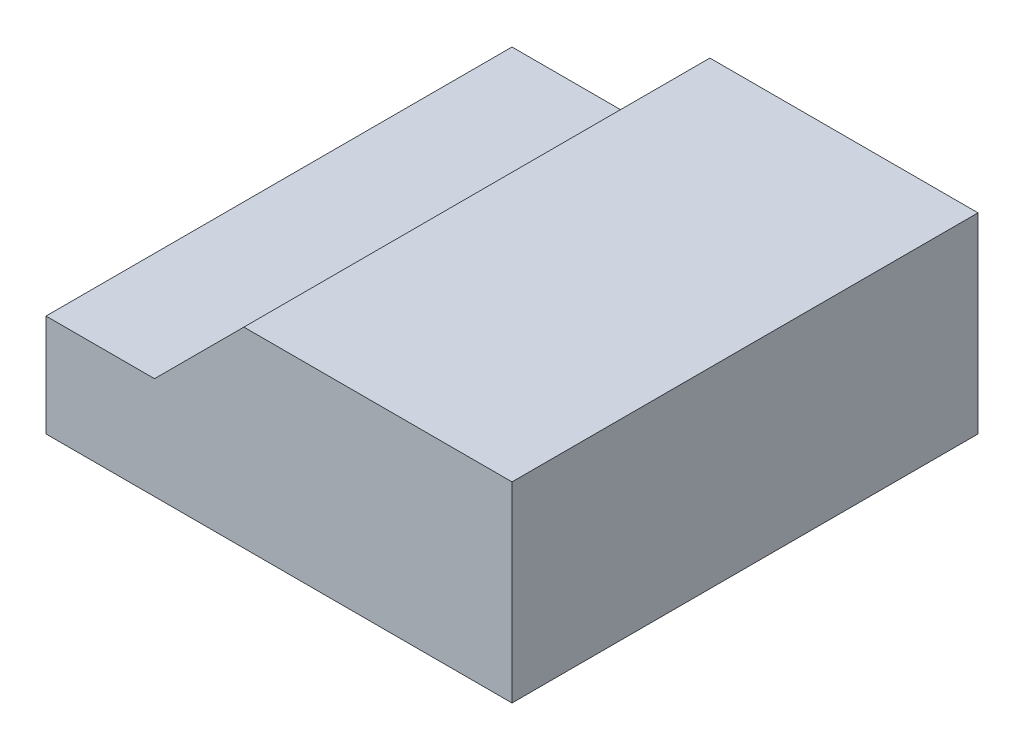
SolidWorks part; units mm, degrees
ref_plane "Front" through (0, 0, 0) normal (0, 0, 1) x (1, 0, 0)
ref_plane "Top" through (0, 0, 0) normal (0, 1, 0) x (1, 0, 0)
ref_plane "Right" through (0, 0, 0) normal (1, 0, 0) x (0, 0, -1)
sketch "Sketch1" plane through (0, 0, 0) normal (0, 0, 1) x (1, 0, 0)
  line L0 (-36.5, -15) -> (36.5, -15)
  line L1 (36.5, -15) -> (36.5, 15)
  line L2 (36.5, 15) -> (-5.5, 15)
  line L3 (-5.5, 15) -> (-19.5, 1)
  line L4 (-19.5, 1) -> (-36.5, 1)
  line L5 (-36.5, 1) -> (-36.5, -15)
  line L6 (-36.5, -15) -> (36.5, 15) construction
  dimension "D1" = 30
  dimension "D2" = 73
  dimension "D3" = 17
  dimension "D4" = 16
  dimension "D5" = 45
extrude "Boss-Extrude1" add sketch "Sketch1" along normal mid plane 73
